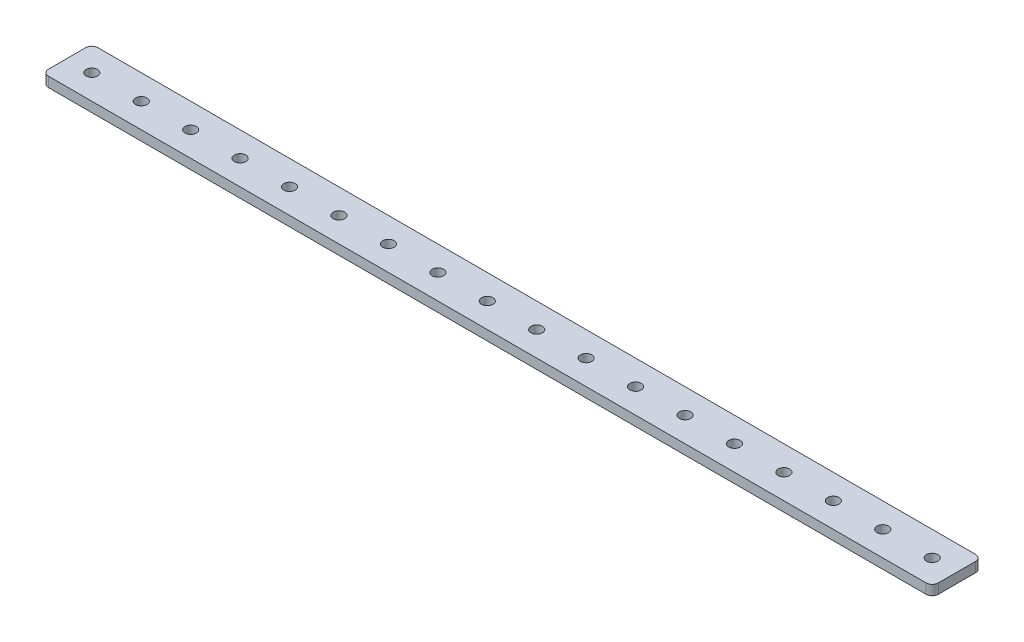
SolidWorks part; units mm, degrees
material "5052 Alloy"
ref_plane "Front Plane" through (0, 0, 0) normal (0, 0, 1) x (1, 0, 0)
ref_plane "Top Plane" through (0, 0, 0) normal (0, 1, 0) x (1, 0, 0)
ref_plane "Right Plane" through (0, 0, 0) normal (1, 0, 0) x (0, 0, -1)
sketch "Sketch1" plane through (0, 0, 0) normal (0, 1, 0) x (1, 0, 0)
  line L1 (0, 0) -> (288, 0)
  line L2 (0, 0) -> (0, 16)
  line L3 (0, 16) -> (288, 16)
  line L4 (288, 0) -> (288, 16)
  dimension "D1" = 288
  dimension "D2" = 16
extrude "Extrude1" add sketch "Sketch1" along normal blind 3.2
sketch "Sketch2" plane through (0, 3.2, 0) normal (0, 1, 0) x (1, 0, 0)
  line L0 (0, 16) -> (0, 0) construction
  line L1 (288, 8) -> (-23.3484, 8) construction
  line L2 (288, 0) -> (288, 16) construction
  line L3 (-23.3484, 8) -> (329.3474, 8) construction
  line L4 (0, 0) -> (288, 0) construction
  circle A0 centre (8, 8) radius 1.85
  circle A1 centre (24, 8) radius 1.85
  circle A2 centre (40, 8) radius 1.85
  circle A3 centre (56, 8) radius 1.85
  circle A4 centre (72, 8) radius 1.85
  circle A5 centre (88, 8) radius 1.85
  circle A6 centre (104, 8) radius 1.85
  circle A7 centre (120, 8) radius 1.85
  circle A8 centre (136, 8) radius 1.85
  circle A9 centre (152, 8) radius 1.85
  circle A10 centre (168, 8) radius 1.85
  circle A11 centre (184, 8) radius 1.85
  circle A12 centre (200, 8) radius 1.85
  circle A13 centre (216, 8) radius 1.85
  circle A14 centre (232, 8) radius 1.85
  circle A15 centre (248, 8) radius 1.85
  circle A16 centre (264, 8) radius 1.85
  circle A17 centre (280, 8) radius 1.85
  dimension "D1" = 3.7
  dimension "D2" = 8
  dimension "D3" = 8
  dimension "D4" = 16
  dimension "D5" = 16
  dimension "D6" = 16
  dimension "D7" = 16
  dimension "D8" = 16
  dimension "D9" = 16
  dimension "D10" = 16
  dimension "D11" = 16
  dimension "D12" = 16
  dimension "D13" = 16
  dimension "D14" = 16
  dimension "D15" = 16
  dimension "D16" = 16
  dimension "D17" = 16
  dimension "D18" = 16
  dimension "D19" = 16
  dimension "D20" = 16
extrude "Cut-Extrude1" cut sketch "Sketch2" against normal through all
fillet "Fillet1" radius 2 1 edges at (288, 1.6, 0)
fillet "Fillet2" radius 2 1 edges at (288, 1.6, -16)
fillet "Fillet3" radius 2 1 edges at (0, 1.6, -16)
fillet "Fillet4" radius 2 1 edges at (0, 1.6, 0)
